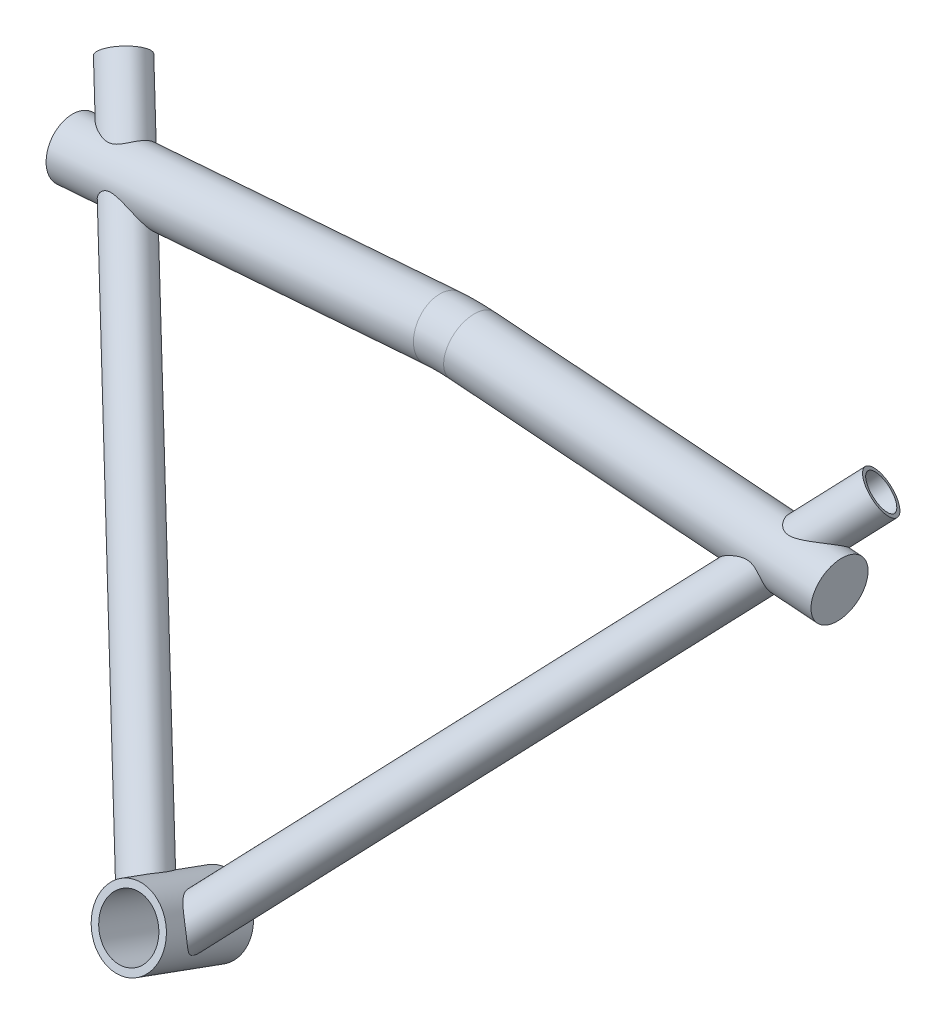
SolidWorks part; units mm, degrees
material "AISI 4130 Steel, normalized at 870C"
ref_plane "Front Plane" through (0, 0, 0) normal (0, 0, 1) x (1, 0, 0)
ref_plane "Top Plane" through (0, 0, 0) normal (0, 1, 0) x (1, 0, 0)
ref_plane "Right Plane" through (0, 0, 0) normal (1, 0, 0) x (0, 0, -1)
sketch "Sketch3" plane through (0, 0, 0) normal (0, 1, 0) x (1, 0, 0)
  line L0 (-5.08, -6.35) -> (5.08, -6.35) construction
  line L2 (0, -88.2205) -> (0, 88.2205) construction
  line L3 (5.08, 0) -> (-5.08, 0) construction
  dimension "D1" = 5.08
  dimension "D2" = 10.16
  dimension "D3" = 6.35
  dimension "D4" = 10.16
  dimension "D5" = 5.08
ref_plane "Plane1" through (0, 3.1441, 3.6169) normal (0, 0.6561, 0.7547) x (1, 0, 0)
ref_plane "Plane3" through (0, 0, 0) normal (0, 0.342, 0.9397) x (-1, 0, 0)
sketch "Sketch1" plane through (0, 0, 0) normal (0, 0.342, 0.9397) x (1, 0, 0)
  circle A0 centre (0, 0) radius 15.875
  dimension "D1" = 31.75
extrude "Boss-Extrude1" add sketch "Sketch1" along normal mid plane 41.402 contours A0
sketch "Sketch4" plane through (0, 3.1441, 3.6169) normal (0, 0.6561, 0.7547) x (1, 0, 0)
  line L0 (-5.08, -4.166) -> (-168.9795, 229.9067)
  line L2 (0, -90.5202) -> (0, 90.5202) construction
  dimension "D2" = 35
  dimension "D3" = 285.75
sweep "Sweep1" add path "Sketch4" circular profile diameter 19.05 parameters "D3"=19.05
sketch "Sketch15" plane through (0, 3.1441, 3.6169) normal (0, 0.6561, 0.7547) x (1, 0, 0)
  line L0 (5.08, -4.166) -> (168.9795, 229.9067)
  line L1 (0, -90.5202) -> (0, 90.5202) construction
  dimension "D1" = 285.75
  dimension "D2" = 35
sweep "Sweep2" add path "Sketch15" circular profile diameter 19.05 parameters "D3"=19.05
sketch "Sketch36" plane through (-163.6134, 176.3485, -153.2974) normal (-0.5736, 0.6182, -0.5374) x (0.8191, 0.4394, -0.3687)
  circle A0 centre (-6.5024, -4.8578) radius 7.9375
  dimension "D1" = 15.875
extrude "Cut-Extrude2" cut sketch "Sketch36" against normal up to surface (295.9599 mm away)
sketch "Sketch37" plane through (163.6134, 176.3485, -153.2974) normal (0.5736, 0.6182, -0.5374) x (0.8191, -0.4394, 0.3687)
  circle A0 centre (6.5024, -4.8578) radius 7.9375
  dimension "D1" = 15.875
extrude "Cut-Extrude3" cut sketch "Sketch37" against normal up to surface (271.2876 mm away)
sketch "Sketch77" plane through (0, 7.0802, 19.4526) normal (0, 0.342, 0.9397) x (1, 0, 0)
  circle A1 centre (0, 0) radius 15.875
extrude "Boss-Extrude2" add sketch "Sketch77" against normal up to surface (41.402 mm away) up to face at (0, -21.9978, -14.023)
sketch "Sketch2" plane through (0, -7.0802, -19.4526) normal (0, -0.342, -0.9397) x (-1, 0, 0)
  circle A0 centre (0, 0) radius 12.7
  dimension "D1" = 25.4
extrude "Cut-Extrude1" cut sketch "Sketch2" against normal up to next
ref_plane "Plane2" through (0, 0, -127) normal (0, 0, 1) x (1, 0, 0)
sketch "Sketch40" plane through (-106.934, 0, -127) normal (0, 0, 1) x (1, 0, 0)
  line L2 (106.934, -85.9333) -> (106.934, 85.9333) construction
  line L3 (100.2024, 162.3048) -> (-63.6638, 149.8608)
  line L4 (113.6656, 162.3048) -> (277.5318, 149.8608)
  arc A0 (100.2024, 162.3048) -> (113.6656, 162.3048) centre (106.934, 73.66) cw
  point P0 (106.934, 162.56)
  point P7 (106.934, 162.56)
  dimension "D1" = 164.338
  dimension "D3" = 88.9
  dimension "D2" = 164.338
  dimension "D4" = 4.75
sweep "Sweep3" add path "Sketch40" circular profile diameter 25.4 parameters "D3"=25.4
